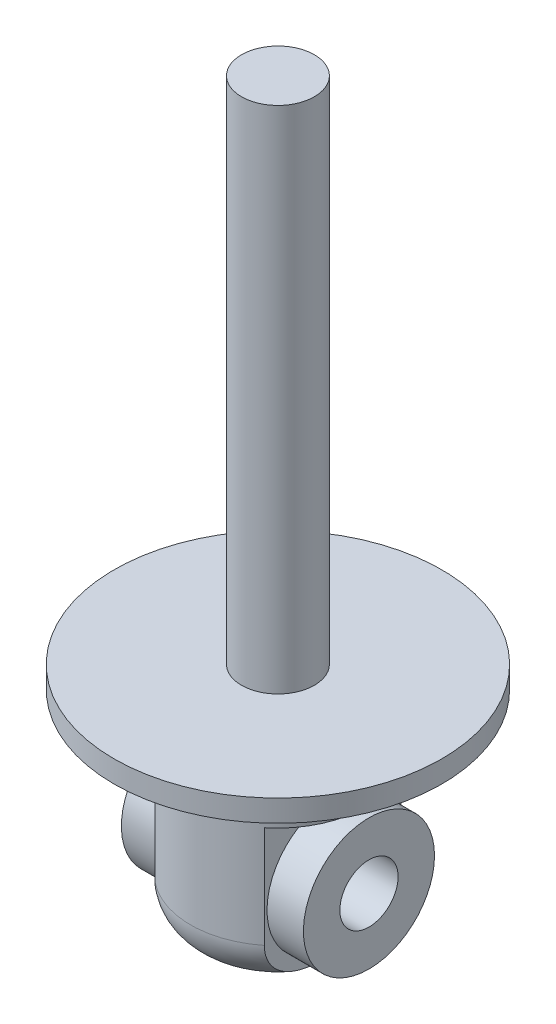
SolidWorks part; units mm, degrees
ref_plane "Front Plane" through (0, 0, 0) normal (0, 0, 1) x (1, 0, 0)
ref_plane "Top Plane" through (0, 0, 0) normal (0, 1, 0) x (1, 0, 0)
ref_plane "Right Plane" through (0, 0, 0) normal (1, 0, 0) x (0, 0, -1)
sketch "Sketch2" plane through (0, 0, 0) normal (0, 1, 0) x (1, 0, 0)
  circle A0 centre (0, 0) radius 22.5
  dimension "D1" = 45
extrude "Boss-Extrude1" add sketch "Sketch2" along normal blind 3
sketch "Sketch3" plane through (0, 3, 0) normal (0, 1, 0) x (1, 0, 0)
  circle A0 centre (0, 0) radius 5
  dimension "D1" = 10
extrude "Boss-Extrude2" add sketch "Sketch3" along normal blind 70
sketch "Sketch4" plane through (0, 0, 0) normal (0, -1, 0) x (1, 0, 0)
  circle A0 centre (0, 0) radius 12
  dimension "D1" = 24
extrude "Boss-Extrude3" add sketch "Sketch4" along normal blind 28
fillet "Fillet1" radius 6 1 edges at (0, -28, -12)
sketch "Sketch5" plane through (0, 0, 0) normal (0, 0, 1) x (1, 0, 0)
  line L0 (0, 0) -> (0, -28) construction
  line L1 (-6, -28) -> (6, -28) construction
  line L2 (7.5, -28) -> (39.823, -28)
  line L3 (39.823, -28) -> (39.823, -8)
  line L4 (39.823, -8) -> (7.5, -8)
  line L5 (7.5, -8) -> (7.5, -28)
  line L6 (-7.5, -8) -> (-7.5, -28)
  line L7 (-39.823, -8) -> (-7.5, -8)
  line L8 (-39.823, -28) -> (-39.823, -8)
  line L9 (-7.5, -28) -> (-39.823, -28)
  dimension "D1" = 15
  dimension "D2" = 20
  dimension "D3" = 32.323
extrude "Cut-Extrude1" cut sketch "Sketch5" against normal through all both and the other way through all
sketch "Sketch6" plane through (7.5, 0, 0) normal (1, 0, 0) x (0, 0, -1)
  line L0 (0, 0) -> (0, -28) construction
  line L1 (-6, -28) -> (6, -28) construction
  circle A0 centre (0, -18) radius 4
  point P7 (0, -16.825)
  point P8 (0, -17.5398)
  point P9 (0, -16.9313)
  point P10 (0, 0)
  point P11 (0, -17.1386)
  point P12 (0, -16.8785)
  dimension "D1" = 8
  dimension "D2" = 10
extrude "Cut-Extrude2" cut sketch "Sketch6" against normal through all both and the other way through all
sketch "Sketch7" plane through (0, 0, 0) normal (1, 0, 0) x (0, 0, -1)
  circle A0 centre (0, -18) radius 9
  circle A1 centre (0, -18) radius 4 construction
  circle A2 centre (0, -18) radius 4
  dimension "D1" = 18
extrude "Boss-Extrude4" add sketch "Sketch7" along normal mid plane 25
